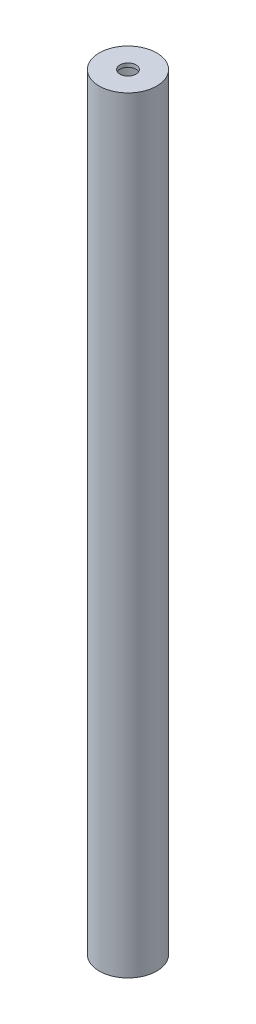
SolidWorks part; units mm, degrees
ref_plane "前视基准面" through (0, 0, 0) normal (0, 0, 1) x (1, 0, 0)
ref_plane "上视基准面" through (0, 0, 0) normal (0, 1, 0) x (1, 0, 0)
ref_plane "右视基准面" through (0, 0, 0) normal (1, 0, 0) x (0, 0, -1)
other "Configuration Table"
sketch "草图1" plane through (0, 0, 0) normal (0, 1, 0) x (1, 0, 0)
  circle A0 centre (0, 0) radius 7.5
  circle A1 centre (0, 0) radius 7
  dimension "D1" = 15
  dimension "D2" = 14
extrude "凸台-拉伸1" add sketch "草图1" along normal blind 200
sketch "草图2" plane through (0, 200, 0) normal (0, 1, 0) x (1, 0, 0)
  circle A1 centre (0, 0) radius 7
extrude "凸台-拉伸2" add sketch "草图2" against normal blind 1
sketch "草图3" plane through (0, 200, 0) normal (0, 1, 0) x (1, 0, 0)
  circle A0 centre (0, 0) radius 2.1
  dimension "D1" = 4.2
extrude "切除-拉伸1" cut sketch "草图3" against normal blind 10
